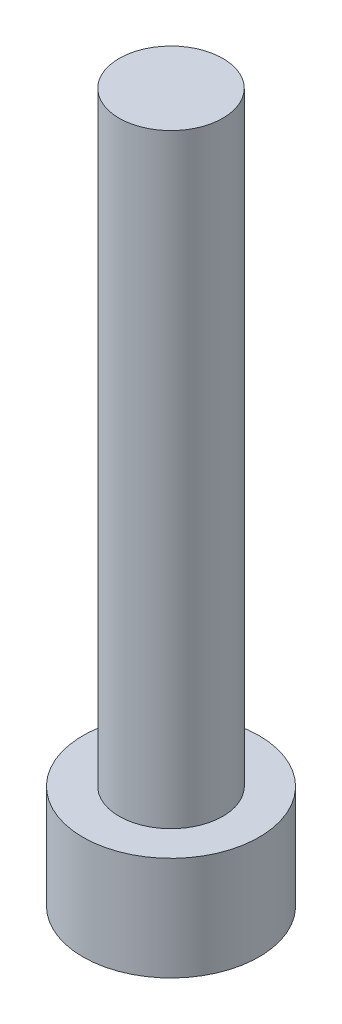
SolidWorks part; units mm, degrees
material "不锈钢 (铁素体)"
ref_plane "前视基准面" through (0, 0, 0) normal (0, 0, 1) x (1, 0, 0)
ref_plane "上视基准面" through (0, 0, 0) normal (0, 1, 0) x (1, 0, 0)
ref_plane "右视基准面" through (0, 0, 0) normal (1, 0, 0) x (0, 0, -1)
sketch "草图1" plane through (0, 0, 0) normal (0, 1, 0) x (1, 0, 0)
  circle A0 centre (0, 0) radius 5.1
  dimension "D1" = 10.2
extrude "凸台-拉伸1" add sketch "草图1" along normal blind 6
sketch "草图2" plane through (0, 6, 0) normal (0, 1, 0) x (1, 0, 0)
  circle A0 centre (0, 0) radius 3
  dimension "D1" = 6
extrude "凸台-拉伸2" add sketch "草图2" along normal blind 35
